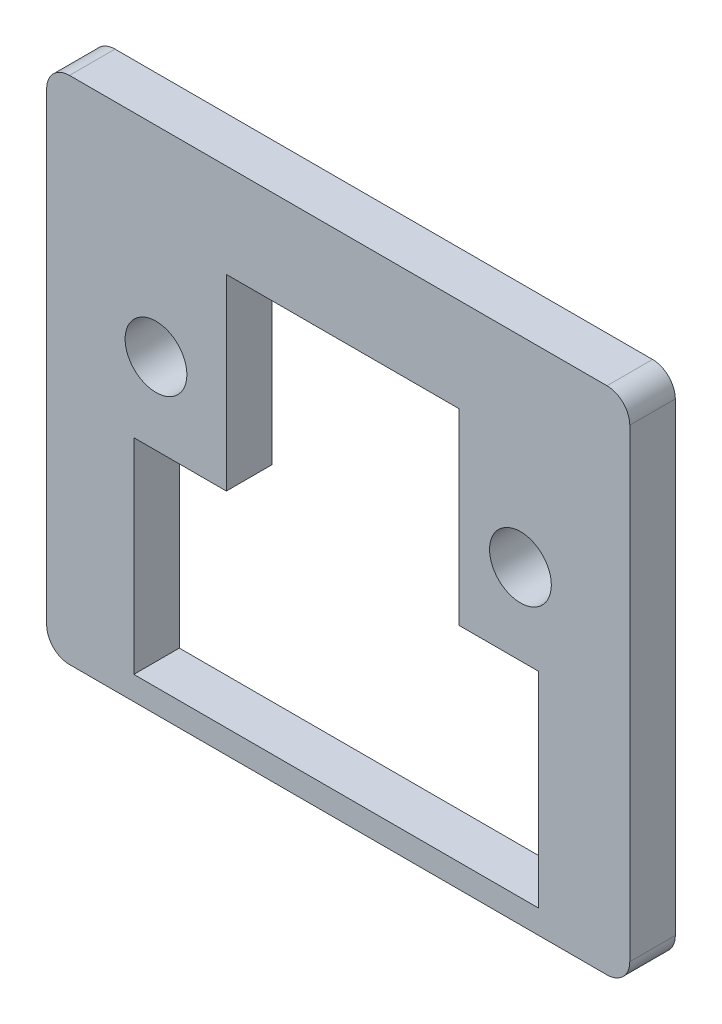
SolidWorks part; units mm, degrees
material "Acrylic (Medium-high impact)"
ref_plane "Front Plane" through (0, 0, 0) normal (0, 0, 1) x (1, 0, 0)
ref_plane "Top Plane" through (0, 0, 0) normal (0, 1, 0) x (1, 0, 0)
ref_plane "Right Plane" through (0, 0, 0) normal (1, 0, 0) x (0, 0, -1)
sketch "Sketch1" plane through (0, 0, 0) normal (0, 0, 1) x (1, 0, 0)
  line L4 (0, 1.5875) -> (0, 33.9725)
  line L5 (-1.5875, 35.56) -> (-39.0525, 35.56)
  line L6 (-40.64, 33.9725) -> (-40.64, 1.5875)
  line L7 (-39.0525, 0) -> (-1.5875, 0)
  line L8 (0, 1.5875) -> (0, 33.9725)
  line L9 (-1.5875, 35.56) -> (-39.0525, 35.56)
  line L10 (-40.64, 33.9725) -> (-40.64, 1.5875)
  line L11 (-39.0525, 0) -> (-1.5875, 0)
  circle A1 centre (-7.62, 21.59) radius 2.1526
  circle A2 centre (-7.62, 21.59) radius 2.1526
  circle A3 centre (-33.02, 21.59) radius 2.1526
  circle A4 centre (-33.02, 21.59) radius 2.1526
  arc A8 (-1.5875, 0) -> (0, 1.5875) centre (-1.5875, 1.5875) ccw
  arc A9 (0, 33.9725) -> (-1.5875, 35.56) centre (-1.5875, 33.9725) ccw
  arc A10 (-39.0525, 35.56) -> (-40.64, 33.9725) centre (-39.0525, 33.9725) ccw
  arc A11 (-40.64, 1.5875) -> (-39.0525, 0) centre (-39.0525, 1.5875) ccw
  arc A12 (-1.5875, 0) -> (0, 1.5875) centre (-1.5875, 1.5875) ccw
  arc A13 (0, 33.9725) -> (-1.5875, 35.56) centre (-1.5875, 33.9725) ccw
  arc A14 (-39.0525, 35.56) -> (-40.64, 33.9725) centre (-39.0525, 33.9725) ccw
  arc A15 (-40.64, 1.5875) -> (-39.0525, 0) centre (-39.0525, 1.5875) ccw
  dimension "D1" = 0
  dimension "D2" = 0
  dimension "D3" = 0
extrude "Boss-Extrude1" add sketch "Sketch1" along normal blind 3.175
sketch "Sketch2" plane through (0, 0, 0) normal (0, 0, -1) x (-1, 0, 0)
  line L0 (11.9186, 15.9395) -> (6.3753, 15.9395)
  line L1 (11.9186, 29.018) -> (28.1151, 29.018)
  line L2 (11.9186, 29.018) -> (11.9186, 15.9395)
  line L4 (28.1151, 29.018) -> (28.1151, 15.9395)
  line L5 (6.3753, 15.9395) -> (6.3753, 1.6484)
  line L6 (6.3753, 1.6484) -> (34.5678, 1.6484)
  line L7 (34.5678, 1.6484) -> (34.5678, 15.9395)
  line L8 (34.5678, 15.9395) -> (28.1151, 15.9395)
extrude "Cut-Extrude1" cut sketch "Sketch2" against normal through all contours L1 L4 L8 L7 L6 L5 L0 L2
